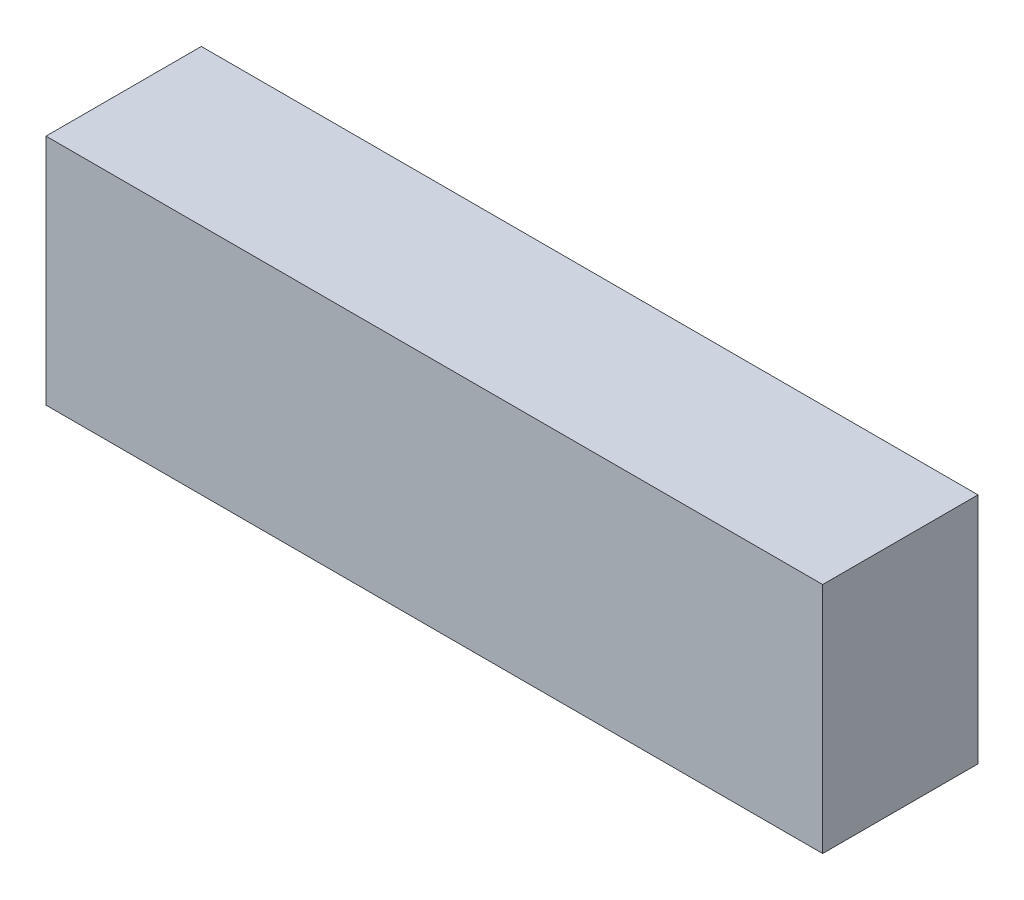
SolidWorks part; units mm, degrees
material "ABS"
ref_plane "Front Plane" through (0, 0, 0) normal (0, 0, 1) x (1, 0, 0)
ref_plane "Top Plane" through (0, 0, 0) normal (0, 1, 0) x (1, 0, 0)
ref_plane "Right Plane" through (0, 0, 0) normal (1, 0, 0) x (0, 0, -1)
sketch "Sketch1" plane through (0, 0, 0) normal (0, 0, 1) x (1, 0, 0)
  line L1 (-50, 15) -> (50, 15)
  line L2 (-50, 15) -> (-50, -15)
  line L3 (-50, -15) -> (50, -15)
  line L4 (50, 15) -> (50, -15)
  line L5 (-50, 15) -> (50, -15) construction
  line L6 (-50, -15) -> (50, 15) construction
  point P0 (0, 0)
  dimension "D1" = 30
  dimension "D2" = 100
extrude "Boss-Extrude1" add sketch "Sketch1" along normal blind 20
